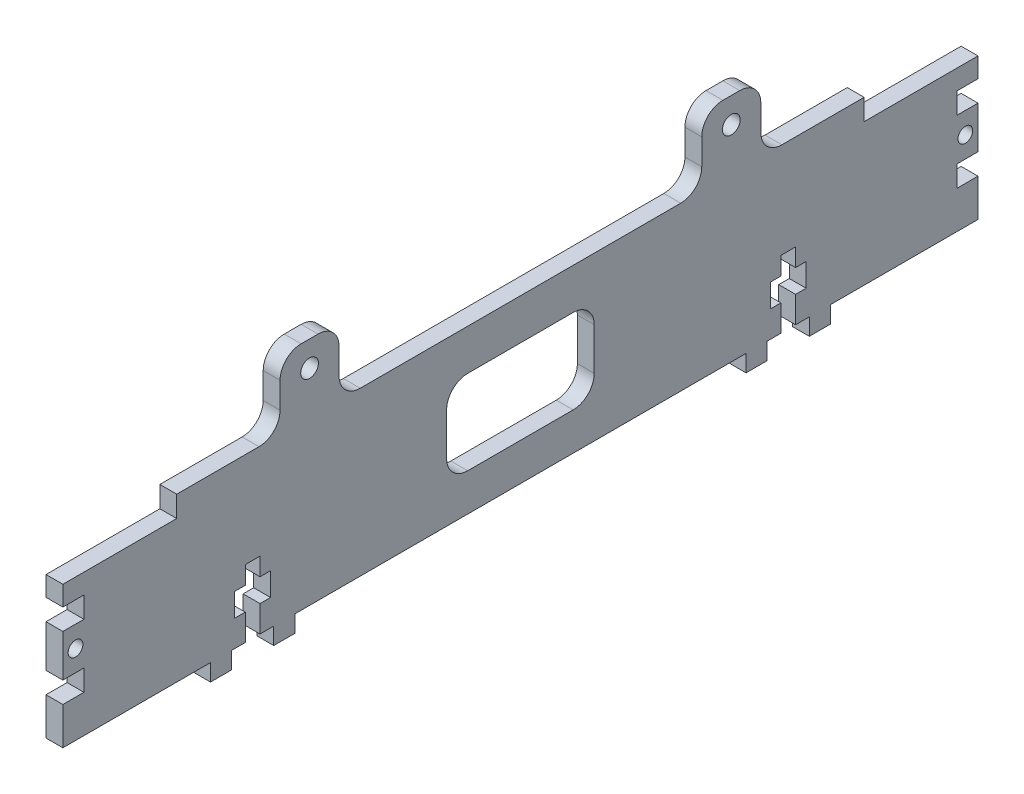
SolidWorks part; units mm, degrees
ref_plane "Plano frontal" through (0, 0, 0) normal (0, 0, 1) x (1, 0, 0)
ref_plane "Plano superior" through (0, 0, 0) normal (0, 1, 0) x (1, 0, 0)
ref_plane "Plano direito" through (0, 0, 0) normal (1, 0, 0) x (0, 0, -1)
sketch "Esboço1" plane through (0, 0, 0) normal (1, 0, 0) x (0, 0, -1)
  line L0 (-105.5, 18.9) -> (-105.5, -18.9) construction
  line L1 (-108.5, 18.9) -> (108.5, 18.9)
  line L2 (-108.5, 18.9) -> (-108.5, 10)
  line L3 (-108.5, -18.9) -> (-73.5, -18.9)
  line L4 (108.5, 18.9) -> (108.5, 10)
  line L5 (-108.5, 18.9) -> (108.5, -18.9) construction
  line L6 (-108.5, -18.9) -> (108.5, 18.9) construction
  line L7 (-108.5, 5) -> (-103.5, 5)
  line L8 (-103.5, 5) -> (-103.5, 10)
  line L9 (-103.5, 10) -> (-108.5, 10)
  line L10 (-108.5, -5) -> (-103.5, -5)
  line L11 (-103.5, -5) -> (-103.5, -10)
  line L12 (-103.5, -10) -> (-108.5, -10)
  line L13 (-103.5, 5) -> (-103.5, -5) construction
  line L14 (-103.5, 0) -> (-105.5, 0) construction
  line L15 (-108.5, 5) -> (-108.5, -5)
  line L16 (-108.5, -10) -> (-108.5, -18.9)
  line L17 (0, 0) -> (0, 11.6282) construction
  line L18 (103.5, -10) -> (108.5, -10)
  line L19 (103.5, -5) -> (103.5, -10)
  line L20 (108.5, -5) -> (103.5, -5)
  line L21 (108.5, 5) -> (103.5, 5)
  line L22 (103.5, 5) -> (103.5, 10)
  line L23 (103.5, 10) -> (108.5, 10)
  line L24 (108.5, 5) -> (108.5, -5)
  line L25 (108.5, -10) -> (108.5, -18.9)
  line L26 (-63.5, -18.9) -> (-63.5, -2.9) construction
  line L27 (-68.5, -18.9) -> (-68.5, -22.9)
  line L29 (-65.25, -18.9) -> (-65.25, -12.65)
  line L30 (-65.25, -2.9) -> (-61.75, -2.9)
  line L31 (-61.75, -18.9) -> (-61.75, -12.65)
  line L32 (-65.25, -18.9) -> (-61.75, -2.9) construction
  line L33 (-65.25, -2.9) -> (-61.75, -18.9) construction
  line L34 (-67.75, -7.15) -> (-65.25, -7.15)
  line L35 (-67.75, -7.15) -> (-67.75, -12.65)
  line L36 (-67.75, -12.65) -> (-65.25, -12.65)
  line L37 (-59.25, -7.15) -> (-59.25, -12.65)
  line L38 (-67.75, -7.15) -> (-59.25, -12.65) construction
  line L39 (-67.75, -12.65) -> (-59.25, -7.15) construction
  line L40 (-68.5, -22.9) -> (-73.5, -22.9)
  line L41 (-73.5, -22.9) -> (-73.5, -18.9)
  line L42 (-58.5, -18.9) -> (-58.5, -22.9)
  line L43 (-58.5, -22.9) -> (-53.5, -22.9)
  line L44 (-53.5, -22.9) -> (-53.5, -18.9)
  line L45 (-68.5, -22.9) -> (-58.5, -22.9) construction
  line L46 (-63.5, -18.9) -> (-63.5, -22.9) construction
  line L47 (-68.5, -18.9) -> (-65.25, -18.9)
  line L48 (-53.5, -18.9) -> (53.5, -18.9)
  line L49 (-61.75, -18.9) -> (-58.5, -18.9)
  line L50 (-61.75, -12.65) -> (-59.25, -12.65)
  line L51 (-61.75, -7.15) -> (-59.25, -7.15)
  line L52 (-61.75, -7.15) -> (-61.75, -2.9)
  line L53 (-65.25, -7.15) -> (-65.25, -2.9)
  line L54 (53.5, -22.9) -> (53.5, -18.9)
  line L55 (58.5, -22.9) -> (53.5, -22.9)
  line L56 (58.5, -18.9) -> (58.5, -22.9)
  line L57 (68.5, -22.9) -> (73.5, -22.9)
  line L58 (73.5, -22.9) -> (73.5, -18.9)
  line L59 (68.5, -18.9) -> (68.5, -22.9)
  line L60 (67.75, -7.15) -> (65.25, -7.15)
  line L61 (67.75, -7.15) -> (67.75, -12.65)
  line L62 (67.75, -12.65) -> (65.25, -12.65)
  line L63 (65.25, -18.9) -> (65.25, -12.65)
  line L64 (61.75, -18.9) -> (61.75, -12.65)
  line L65 (61.75, -12.65) -> (59.25, -12.65)
  line L66 (59.25, -7.15) -> (59.25, -12.65)
  line L67 (61.75, -7.15) -> (59.25, -7.15)
  line L68 (61.75, -7.15) -> (61.75, -2.9)
  line L69 (65.25, -2.9) -> (61.75, -2.9)
  line L70 (65.25, -7.15) -> (65.25, -2.9)
  line L71 (58.5, -18.9) -> (61.75, -18.9)
  line L72 (65.25, -18.9) -> (68.5, -18.9)
  line L73 (73.5, -18.9) -> (108.5, -18.9)
  circle A0 centre (-105.5, 0) radius 1.75
  circle A1 centre (105.5, 0) radius 1.75
  point P0 (0, 0)
  point P33 (-63.5, -10.9)
  point P38 (-63.5, -9.9)
  dimension "D3" = 3.5
  dimension "D1" = 217
  dimension "D2" = 37.8
  dimension "D4" = 5
  dimension "D5" = 5
  dimension "D6" = 10
  dimension "D7" = 2
  dimension "D8" = 16
  dimension "D9" = 45
  dimension "D10" = 3.5
  dimension "D11" = 5.5
  dimension "D12" = 8.5
  dimension "D13" = 7
  dimension "D14" = 5
  dimension "D15" = 4
  dimension "D16" = 10
extrude "Ressalto-extrusão1" add sketch "Esboço1" along normal blind 4
sketch "Esboço2" plane through (4, 0, 0) normal (1, 0, 0) x (0, 0, -1)
  line L0 (0, 18.9) -> (0, -18.9) construction
  line L1 (108.5, 18.9) -> (-108.5, 18.9) construction
  line L2 (-53.5, -18.9) -> (53.5, -18.9) construction
  line L4 (-17.5, 10) -> (17.5, 10)
  line L5 (-17.5, 10) -> (-17.5, -10)
  line L6 (-17.5, -10) -> (17.5, -10)
  line L7 (17.5, 10) -> (17.5, -10)
  line L8 (-17.5, 10) -> (17.5, -10) construction
  line L9 (-17.5, -10) -> (17.5, 10) construction
  point P6 (0, 0)
  dimension "D1" = 20
  dimension "D2" = 35
extrude "Corte-extrusão1" cut sketch "Esboço2" against normal through all
sketch "Esboço3" plane through (4, 0, 0) normal (1, 0, 0) x (0, 0, -1)
  line L0 (-108.5, 18.9) -> (-108.5, 20.69)
  line L1 (-108.5, 20.69) -> (108.5, 20.69)
  line L2 (108.5, 20.69) -> (108.5, 18.9)
  line L3 (108.5, 18.9) -> (-108.5, 18.9)
  dimension "D1" = 1.79
extrude "Ressalto-extrusão2" add sketch "Esboço3" against normal through all
sketch "Esboço4" plane through (4, 0, 0) normal (1, 0, 0) x (0, 0, -1)
  line L0 (-108.5, 14.69) -> (-81.5, 14.69)
  line L1 (-108.5, 20.69) -> (-108.5, 10) construction
  line L2 (-81.5, 14.69) -> (-81.5, 20.69)
  line L3 (108.5, 20.69) -> (-108.5, 20.69) construction
  line L4 (-108.5, 14.69) -> (-108.5, 20.69)
  line L5 (-108.5, 20.69) -> (-81.5, 20.69)
  line L6 (0, 0) -> (0, 20.69) construction
  line L7 (108.5, 14.69) -> (108.5, 20.69)
  line L8 (108.5, 14.69) -> (81.5, 14.69)
  line L9 (81.5, 14.69) -> (81.5, 20.69)
  line L10 (108.5, 20.69) -> (81.5, 20.69)
  dimension "D1" = 6
  dimension "D2" = 27
extrude "Corte-extrusão2" cut sketch "Esboço4" against normal through all
sketch "Esboço5" plane through (4, 0, 0) normal (1, 0, 0) x (0, 0, -1)
  line L0 (-81.5, 20.69) -> (81.5, 20.69)
  line L1 (81.5, 20.69) -> (81.5, 19.69)
  line L2 (81.5, 20.69) -> (81.5, 14.69) construction
  line L3 (81.5, 19.69) -> (-81.5, 19.69)
  line L4 (-81.5, 14.69) -> (-81.5, 20.69) construction
  line L5 (-81.5, 19.69) -> (-81.5, 20.69)
  dimension "D1" = 1
extrude "Corte-extrusão3" cut sketch "Esboço5" against normal through all
sketch "Esboço6" plane through (4, 0, 0) normal (1, 0, 0) x (0, 0, -1)
  line L0 (0, 0) -> (0, 38.7571) construction
  line L1 (-50, 19.69) -> (-50, 29.82) construction
  line L2 (-81.5, 19.69) -> (81.5, 19.69) construction
  line L3 (-57, 19.69) -> (-57, 30.82)
  line L4 (-52, 35.82) -> (-48, 35.82)
  line L5 (-43, 30.82) -> (-43, 19.69)
  line L6 (-43, 19.69) -> (-57, 19.69)
  line L7 (43, 30.82) -> (43, 19.69)
  line L8 (52, 35.82) -> (48, 35.82)
  line L9 (57, 19.69) -> (57, 30.82)
  line L10 (43, 19.69) -> (57, 19.69)
  circle A0 centre (-50, 29.82) radius 2.1
  arc A2 (-48, 35.82) -> (-43, 30.82) centre (-48, 30.82) cw
  arc A3 (-57, 30.82) -> (-52, 35.82) centre (-52, 30.82) cw
  circle A4 centre (50, 29.82) radius 2.1
  arc A5 (48, 35.82) -> (43, 30.82) centre (48, 30.82) ccw
  arc A6 (57, 30.82) -> (52, 35.82) centre (52, 30.82) ccw
  dimension "D1" = 50
  dimension "D2" = 4.2
  dimension "D4" = 6
  dimension "D7" = 5
  dimension "D3" = 10.13
  dimension "D5" = 7
  dimension "D6" = 7
extrude "Ressalto-extrusão4" add sketch "Esboço6" against normal through all
fillet "Filete1" radius 5 4 edges at (2, 19.69, -57) (2, 19.69, -43) (2, 19.69, 57) (2, 19.69, 43)
fillet "Filete2" radius 5 4 edges at (2, -10, 17.5) (2, -10, -17.5) (2, 10, -17.5) (2, 10, 17.5)
